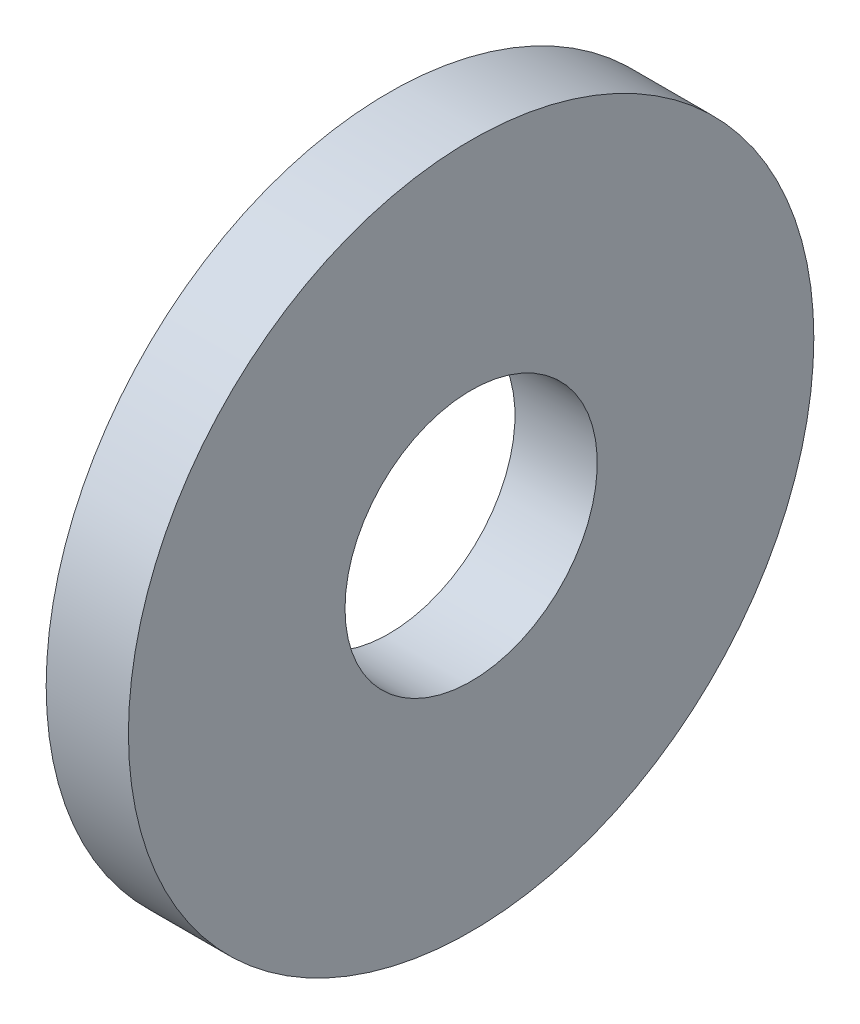
SolidWorks part; units mm, degrees
material "Alloy Steel"
ref_plane "Plane1" through (0, 0, 0) normal (0, 0, 1) x (1, 0, 0)
ref_plane "Plane2" through (0, 0, 0) normal (0, 1, 0) x (1, 0, 0)
ref_plane "Plane3" through (0, 0, 0) normal (1, 0, 0) x (0, 0, -1)
revolve "Base-Revolve" add sketch "Sketch1" angle 360 about L0
sketch "Sketch1" plane through (0, 0, 0) normal (0, 0, 1) x (1, 0, 0)
  line L0 (-34.925, 0) -> (9.525, 0) construction
  line L1 (0, 1.84) -> (0, 5)
  line L2 (0, 5) -> (-1.2, 5)
  line L3 (-1.2, 5) -> (-1.2, 1.84)
  line L4 (-1.2, 1.84) -> (0, 1.84)
  dimension "Thickness" = 1.2
  dimension "Inside_dia" = 3.68
  dimension "Outside_dia" = 10
